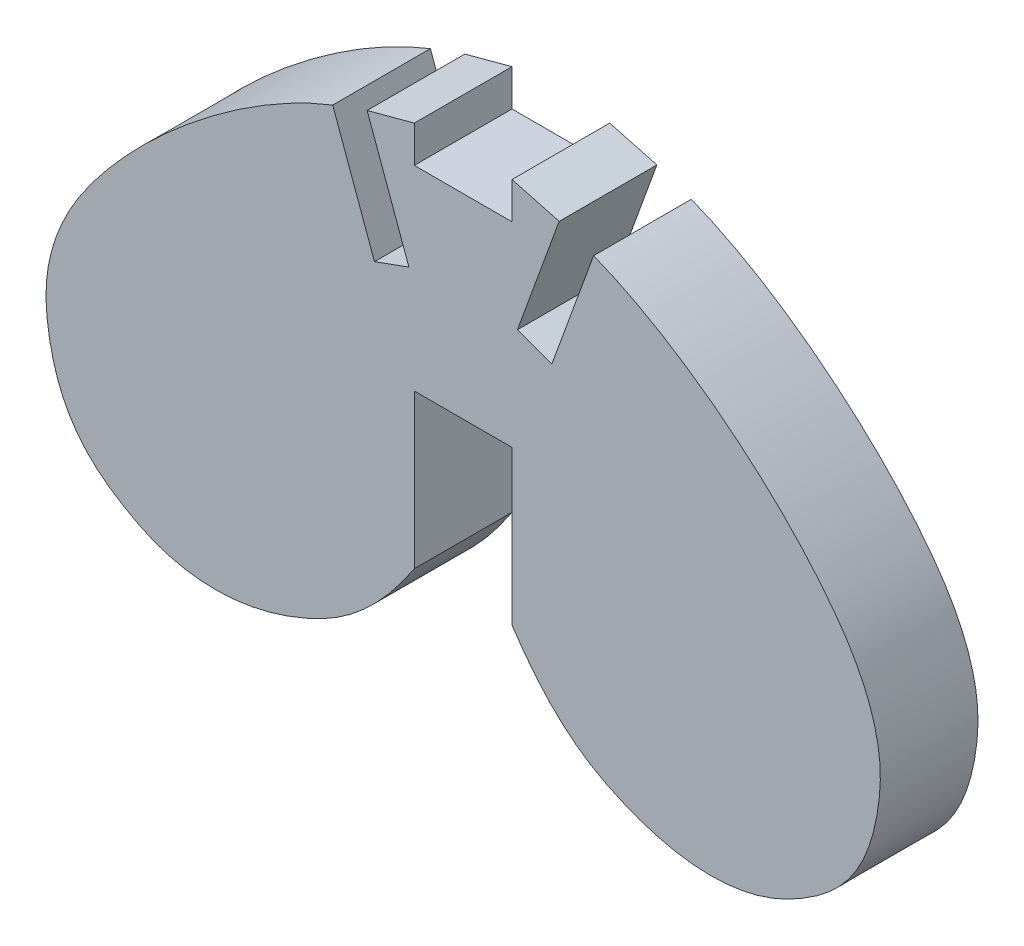
SolidWorks part; units mm, degrees
ref_plane "Piano frontale" through (0, 0, 0) normal (0, 0, 1) x (1, 0, 0)
ref_plane "Piano superiore" through (0, 0, 0) normal (0, 1, 0) x (1, 0, 0)
ref_plane "Piano destro" through (0, 0, 0) normal (1, 0, 0) x (0, 0, -1)
sketch "Schizzo1" plane through (0, 0, 0) normal (0, 0, 1) x (1, 0, 0)
  line L0 (2, 0) -> (-2, 0)
  line L1 (-2, 0) -> (-2, -8)
  line L2 (2, 0) -> (2, -8)
  line L3 (2, -8) -> (12, -8)
  line L4 (12, -8) -> (12, 3)
  line L5 (12, 3) -> (5.3414, 8.4693)
  line L6 (5.3414, 8.4693) -> (3.6313, 3.7709)
  line L7 (3.6313, 3.7709) -> (2.2218, 4.2839)
  line L8 (2.2218, 4.2839) -> (3.9319, 8.9824)
  line L9 (3.9319, 8.9824) -> (2, 9.5)
  line L10 (2, 9.5) -> (2, 8)
  line L11 (2, 8) -> (-2, 8)
  line L12 (-2, 8) -> (-2, 9.5)
  line L13 (-2, 9.5) -> (-3.9319, 8.9824)
  line L14 (-3.9319, 8.9824) -> (-2.2218, 4.2839)
  line L15 (-2.2218, 4.2839) -> (-3.6313, 3.7709)
  line L16 (-3.6313, 3.7709) -> (-5.3414, 8.4693)
  line L17 (-5.3414, 8.4693) -> (-12, 3)
  line L18 (-12, 3) -> (-12, -8)
  line L19 (-12, -8) -> (-2, -8)
  line L20 (0, 0) -> (0, 8)
  spline S0 degree 3 poles (-5.3414, 8.4693) (-8.5372, 7.2223) (-12.884, 3.9257) (-16.4867, -0.9549) (-17.2144, -3.292) (-16.7703, -7.608) (-15.2378, -9.3515) (-11.4361, -11.3722) (-8.7584, -11.1538) (-5.6311, -10.0079) (-3.7099, -8.8982) (-2, -6.3022) knots 0 0 0 0 0.182311 0.212904 0.295596 0.328759 0.511374 0.559298 0.760079 0.806659 1 1 1 1
  spline S1 degree 3 poles (8.6457, 5.6742) (13.1177, 2.0285) (16.4146, -4.4065) (6.8401, -10.6168) (3.6722, -7.5593) (2, -6.3022) knots 0 0 0 0 0.41228 0.671229 1 1 1 1
  spline S2 degree 3 poles (-8.6457, 5.6742) (-13.1177, 2.0285) (-16.4146, -4.4065) (-6.8401, -10.6168) (-3.6722, -7.5593) (-2, -6.3022) knots 0 0 0 0 0.41228 0.671229 1 1 1 1
  spline S3 degree 3 poles (5.3414, 8.4693) (8.5372, 7.2223) (12.884, 3.9257) (16.4867, -0.9549) (17.2144, -3.292) (16.7703, -7.608) (15.2378, -9.3515) (11.4361, -11.3722) (8.7584, -11.1538) (5.6311, -10.0079) (3.7099, -8.8982) (2, -6.3022) knots 0 0 0 0 0.182311 0.212904 0.295596 0.328759 0.511374 0.559298 0.760079 0.806659 1 1 1 1
  point P0 (0, 8)
  point P4 (0, 0)
  dimension "D1" = 4
  dimension "D2" = 10
  dimension "D3" = 10
  dimension "D4" = 8
  dimension "D5" = 8
  dimension "D6" = 8
  dimension "D7" = 4
  dimension "D8" = 1.5
  dimension "D9" = 1.5
  dimension "D10" = 2
  dimension "D11" = 2
  dimension "D12" = 75
  dimension "D13" = 75
  dimension "D14" = 5
  dimension "D15" = 5
  dimension "D16" = 5
  dimension "D17" = 1.5
  dimension "D18" = 1.5
  dimension "D19" = 85
  dimension "D20" = 85
  dimension "D21" = 5
  dimension "D22" = 11
  dimension "D23" = 11
extrude "Estrusione-Estrusione1" add sketch "Schizzo1" along normal blind 4
